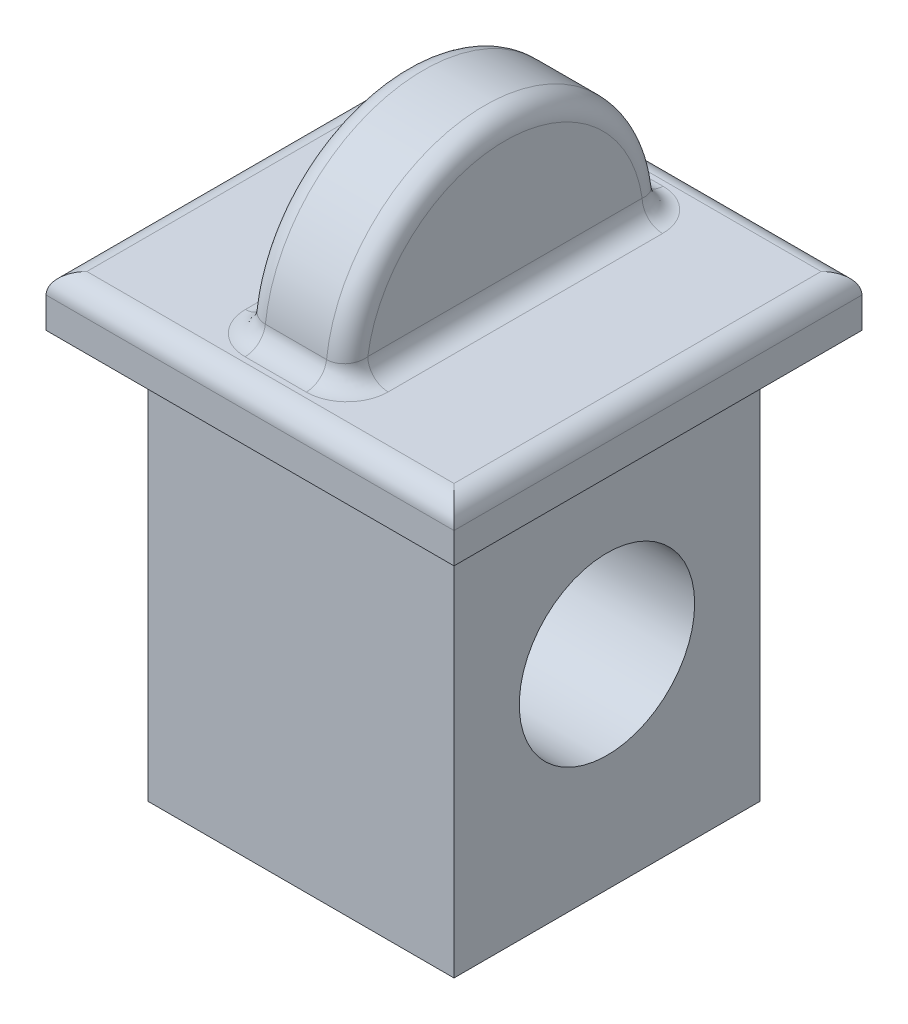
SolidWorks part; units mm, degrees
material "ABS"
ref_plane "Front Plane" through (0, 0, 0) normal (0, 0, 1) x (1, 0, 0)
ref_plane "Top Plane" through (0, 0, 0) normal (0, 1, 0) x (1, 0, 0)
ref_plane "Right Plane" through (0, 0, 0) normal (1, 0, 0) x (0, 0, -1)
sketch "Sketch1" plane through (0, 0, 0) normal (0, 1, 0) x (1, 0, 0)
  line L1 (9.525, -9.525) -> (-9.525, -9.525)
  line L2 (9.525, -9.525) -> (9.525, 9.525)
  line L3 (9.525, 9.525) -> (-9.525, 9.525)
  line L4 (-9.525, -9.525) -> (-9.525, 9.525)
  line L5 (9.525, -9.525) -> (-9.525, 9.525) construction
  line L6 (9.525, 9.525) -> (-9.525, -9.525) construction
  point P0 (0, 0)
  dimension "D1" = 19.05
  dimension "D2" = 19.05
extrude "Boss-Extrude1" add sketch "Sketch1" along normal blind 27.94 contours L3 L4 L1 L2
sketch "Sketch2" plane through (0, 27.94, 0) normal (0, 1, 0) x (1, 0, 0)
  line L4 (9.525, 12.7) -> (9.525, -12.7)
  line L5 (9.525, -9.525) -> (9.525, 9.525) construction
  line L8 (12.7, -12.7) -> (12.7, 12.7)
  line L9 (12.7, 12.7) -> (-12.7, 12.7)
  line L10 (-12.7, 12.7) -> (-12.7, -12.7)
  line L11 (-12.7, -12.7) -> (12.7, -12.7)
  line L12 (12.7, -12.7) -> (12.7, 12.7)
  line L13 (12.7, 12.7) -> (-12.7, 12.7)
  line L14 (-12.7, 12.7) -> (-12.7, -12.7)
  line L15 (-12.7, -12.7) -> (12.7, -12.7)
  line M5 (9.525, -9.525) -> (9.525, 9.525)
  line M6 (9.525, 9.525) -> (-9.525, 9.525)
  line M7 (-9.525, 9.525) -> (-9.525, -9.525)
  line M8 (-9.525, -9.525) -> (9.525, -9.525)
  dimension "D1" = 3.175
extrude "Boss-Extrude2" add sketch "Sketch2" along normal blind 3.175 contours L14 L15 L4 L13 M8 M7 M6 | M8 M5 M6 M7
sketch "Sketch3" plane through (9.525, 0, 0) normal (1, 0, 0) x (0, 0, -1)
  line L2 (-12.7, 27.94) -> (12.7, 27.94) construction
  circle A0 centre (0, 15.24) radius 5.461
  dimension "D1" = 12.7
  dimension "D2" = 10.922
extrude "Cut-Extrude1" cut sketch "Sketch3" against normal through all
sketch "Sketch4" plane through (0, 0, 0) normal (1, 0, 0) x (0, 0, -1)
  line L1 (-9.906, 31.115) -> (9.906, 31.115)
  line L3 (-12.7, 31.115) -> (-12.7, 27.94) construction
  line L4 (-12.7, 31.115) -> (12.7, 31.115) construction
  circle A0 centre (0, 31.115) radius 9.906
  point P9 (0, 31.115)
  dimension "D1" = 2.794
extrude "Boss-Extrude3" add sketch "Sketch4" along normal mid plane 6.35 contours A0
fillet "Fillet1" radius 1.27 10 edges at (-3.175, 41.021, 0) (3.175, 41.021, 0) (-3.175, 31.115, 0) (0, 31.115, -9.906) (0, 31.115, 9.906) (3.175, 31.115, 0) (0, 31.115, -12.7) (0, 31.115, 12.7) (-12.7, 31.115, 0) (12.7, 31.115, 0)
chamfer "Chamfer1" distance 2.54 angle 45 4 edges at (0, 0, -9.525) (-9.525, 0, 0) (0, 0, 9.525) (9.525, 0, 0)
